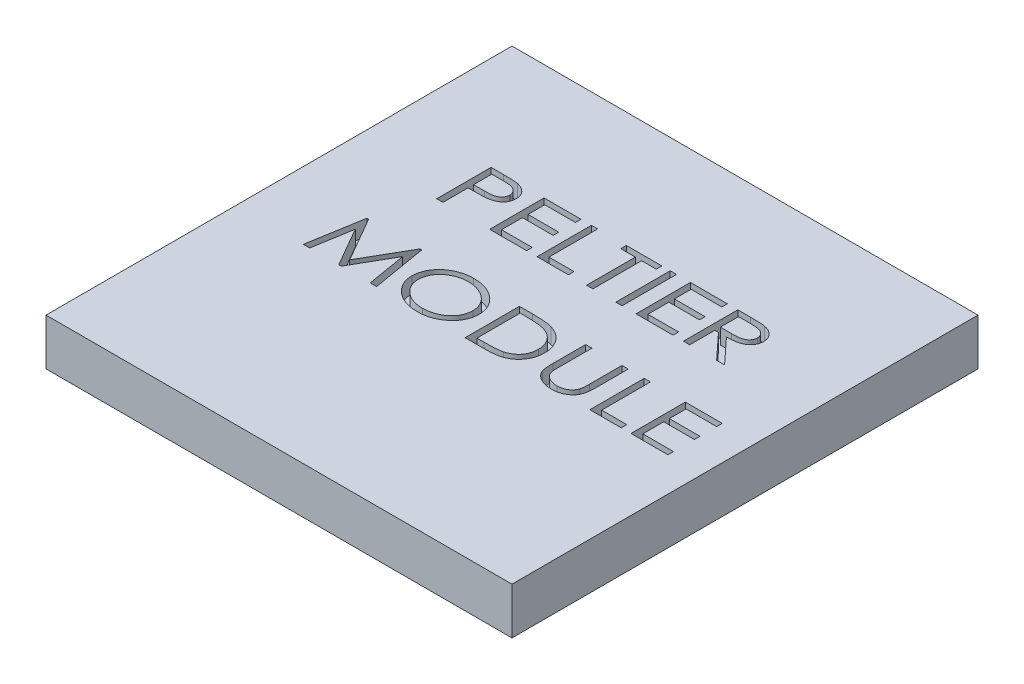
SolidWorks part; units mm, degrees
material "Custom Plastic"
ref_plane "Front Plane" through (0, 0, 0) normal (0, 0, 1) x (1, 0, 0)
ref_plane "Top Plane" through (0, 0, 0) normal (0, 1, 0) x (1, 0, 0)
ref_plane "Right Plane" through (0, 0, 0) normal (1, 0, 0) x (0, 0, -1)
sketch "Sketch1" plane through (0, 0, 0) normal (0, 1, 0) x (1, 0, 0)
  line L1 (-15, -15) -> (15, -15)
  line L2 (-15, -15) -> (-15, 15)
  line L3 (-15, 15) -> (15, 15)
  line L4 (15, -15) -> (15, 15)
  line L5 (-15, -15) -> (15, 15) construction
  line L6 (-15, 15) -> (15, -15) construction
  point P0 (0, 0)
  dimension "D1" = 30
  dimension "D2" = 30
extrude "Boss-Extrude1" add sketch "Sketch1" along normal blind 3
sketch "Sketch2" plane through (0, 3, 0) normal (0, 1, 0) x (1, 0, 0)
  text T0 " PELTIER \r\nMODULE" font "Century Gothic" height 3.5
extrude "Cut-Extrude1" cut sketch "Sketch2" against normal blind 1
